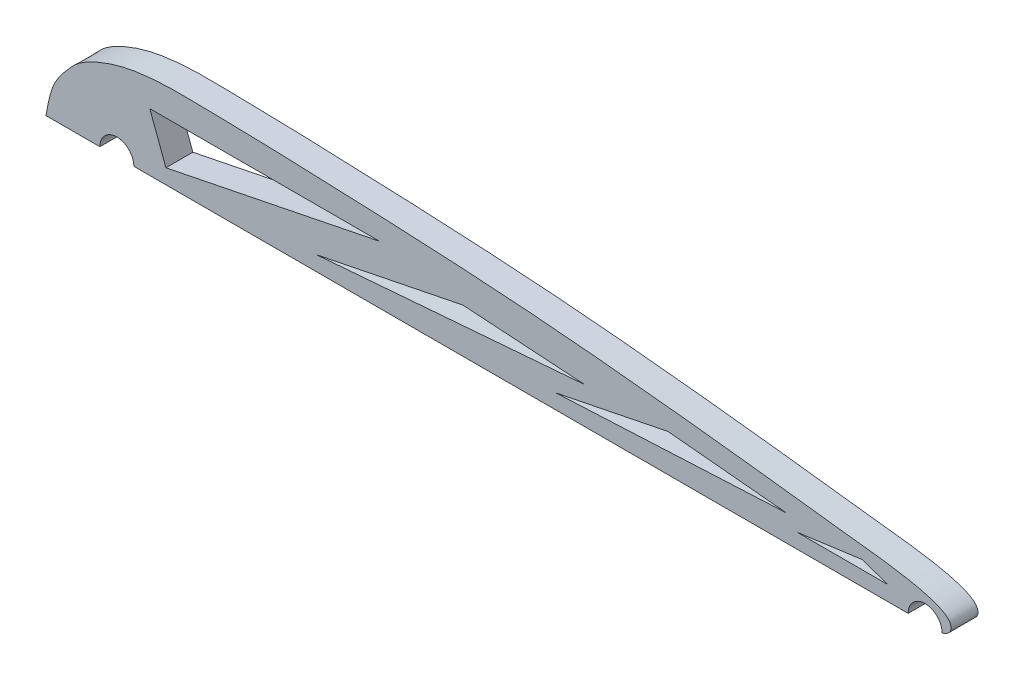
SolidWorks part; units mm, degrees
ref_plane "Front Plane" through (0, 0, 0) normal (0, 0, 1) x (1, 0, 0)
ref_plane "Top Plane" through (0, 0, 0) normal (0, 1, 0) x (1, 0, 0)
ref_plane "Right Plane" through (0, 0, 0) normal (1, 0, 0) x (0, 0, -1)
sketch "草圖1" plane through (0, 0, 0) normal (0, 0, 1) x (1, 0, 0)
  line L0 (-75, 0) -> (75, 0) construction
  line L1 (-88.15, 0) -> (-78.15, 0)
  line L2 (-71.85, 0) -> (71.85, 0)
  line L3 (-68.8935, 10.7598) -> (-65.8996, 2.7429)
  line L4 (-65.8996, 2.7429) -> (-26.2304, 10.7598)
  line L5 (-26.2304, 10.7598) -> (-68.8935, 10.7598)
  line L6 (-37.9565, 2.7429) -> (-10.7862, 8.2339)
  line L7 (-10.7862, 8.2339) -> (11.8172, 6.7514)
  line L8 (11.8172, 6.7514) -> (-37.9565, 2.7429)
  line L9 (6.4531, 2.7429) -> (27.2662, 6.9491)
  line L10 (27.2662, 6.9491) -> (49.241, 4.846)
  line L11 (49.241, 4.846) -> (6.4531, 2.7429)
  line L12 (51.2686, 2.7429) -> (63.2976, 4.3862)
  line L13 (63.2976, 4.3862) -> (68.1092, 2.7429)
  line L14 (68.1092, 2.7429) -> (51.2686, 2.7429)
  arc A0 (-71.85, 0) -> (-78.15, 0) centre (-75, 0) ccw
  arc A1 (78.15, 0) -> (71.85, 0) centre (75, 0) ccw
  spline S0 degree 3 poles (-88.15, 0) (-87.22, 5.7384) (-86.1626, 7.0953) (-81.5993, 12.2675) (-75.9493, 14.6152) (-66.8998, 16.2433) (-61.1397, 15.8791) (-48.1351, 15.7694) (-10.4279, 14.3483) (10.4925, 12.6102) (40.2083, 9.5739) (42.9698, 9.07) (64.9906, 6.47) (81.3237, 4.8738) (79.7288, 0.4272) (78.15, 0) knots 0 0 0 0 0.103555 0.121163 0.169973 0.187492 0.278836 0.301421 0.401931 0.510006 0.543484 0.715238 0.759475 0.941619 1 1 1 1
  dimension "D1" = 6.3
  dimension "D2" = 75
  dimension "D3" = 10
extrude "填料-伸長1" add sketch "草圖1" along normal blind 5
